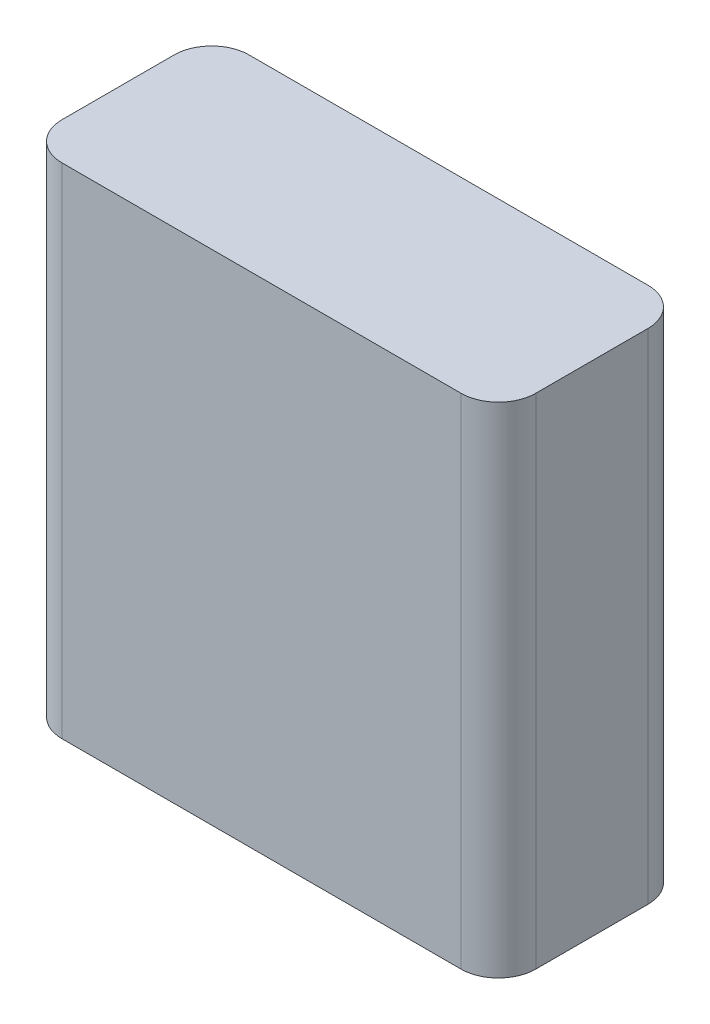
SolidWorks part; units mm, degrees
material "Thornel Mat VMA"
ref_plane "Front Plane" through (0, 0, 0) normal (0, 0, 1) x (1, 0, 0)
ref_plane "Top Plane" through (0, 0, 0) normal (0, 1, 0) x (1, 0, 0)
ref_plane "Right Plane" through (0, 0, 0) normal (1, 0, 0) x (0, 0, -1)
sketch "Sketch1" plane through (0, 0, 0) normal (0, 1, 0) x (1, 0, 0)
  line L1 (-406.4, -190.5) -> (406.4, -190.5)
  line L2 (-482.6, -114.3) -> (-482.6, 114.3)
  line L3 (-406.4, 190.5) -> (406.4, 190.5)
  line L4 (482.6, -114.3) -> (482.6, 114.3)
  line L5 (-482.6, -190.5) -> (482.6, 190.5) construction
  line L6 (-482.6, 190.5) -> (482.6, -190.5) construction
  arc A0 (406.4, 190.5) -> (482.6, 114.3) centre (406.4, 114.3) cw
  arc A1 (482.6, -114.3) -> (406.4, -190.5) centre (406.4, -114.3) cw
  arc A2 (-406.4, -190.5) -> (-482.6, -114.3) centre (-406.4, -114.3) cw
  arc A3 (-406.4, 190.5) -> (-482.6, 114.3) centre (-406.4, 114.3) ccw
  point P0 (0, 0)
  dimension "D3" = 76.2
  dimension "D1" = 965.2
  dimension "D2" = 381
extrude "Boss-Extrude1" add sketch "Sketch1" along normal blind 1016
